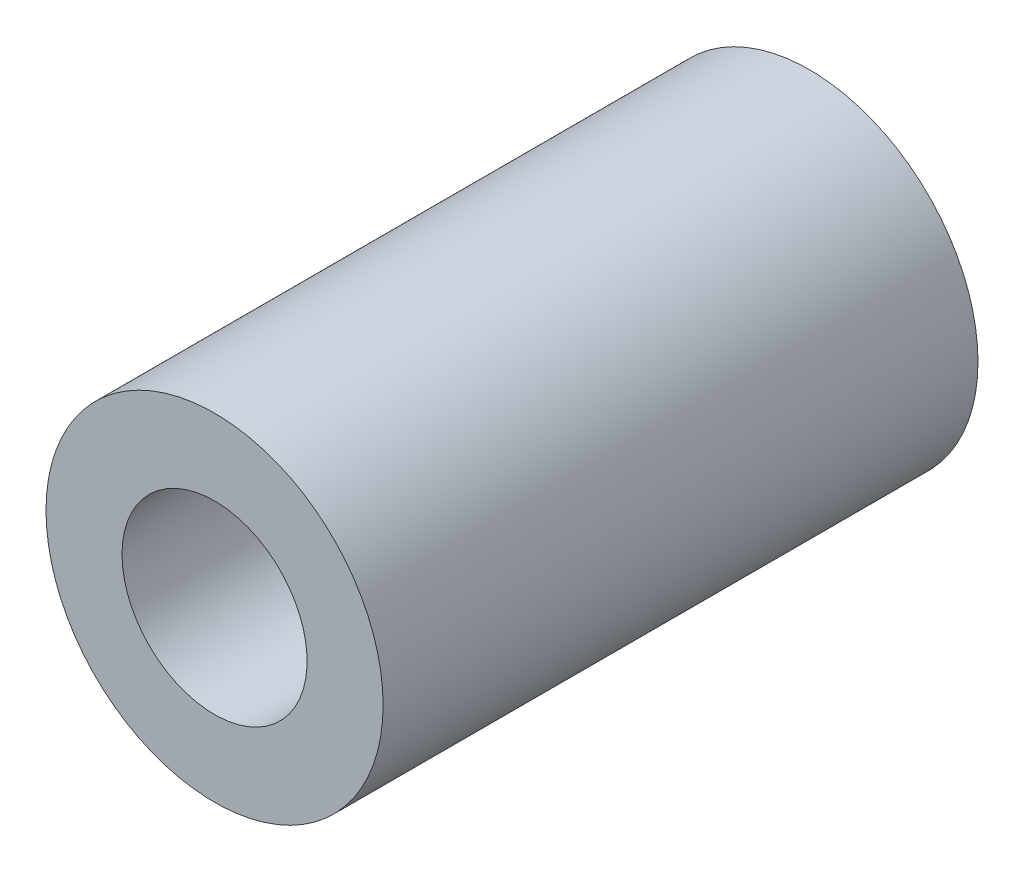
SolidWorks part; units mm, degrees
ref_plane "前视基准面" through (0, 0, 0) normal (0, 0, 1) x (1, 0, 0)
ref_plane "上视基准面" through (0, 0, 0) normal (0, 1, 0) x (1, 0, 0)
ref_plane "右视基准面" through (0, 0, 0) normal (1, 0, 0) x (0, 0, -1)
other "Configuration Table"
sketch "草图1" plane through (0, 0, 0) normal (0, 0, 1) x (1, 0, 0)
  circle A0 centre (0, 0) radius 7
  circle A1 centre (0, 0) radius 12.75
  dimension "D1" = 14
  dimension "D2" = 25.5
extrude "凸台-拉伸1" add sketch "草图1" along normal blind 45
